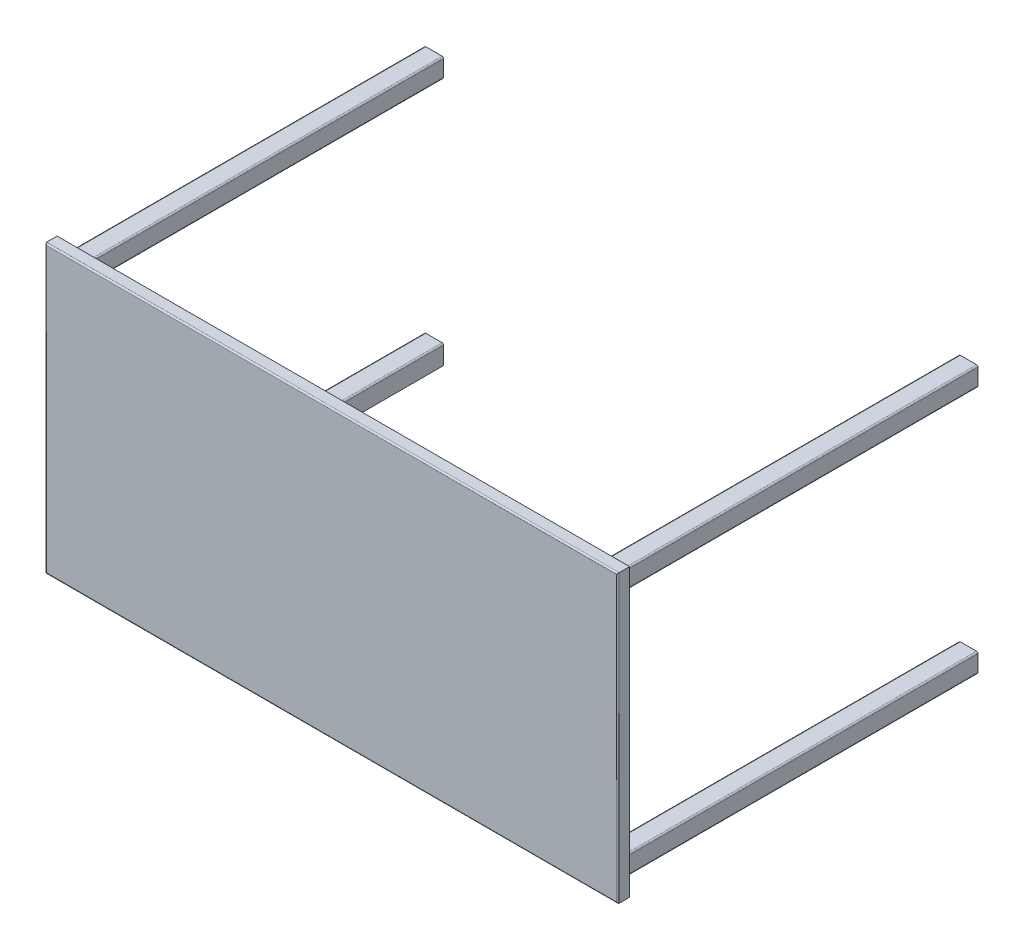
SolidWorks part; units mm, degrees
ref_plane "前视基准面" through (0, 0, 0) normal (0, 0, 1) x (1, 0, 0)
ref_plane "上视基准面" through (0, 0, 0) normal (0, 1, 0) x (1, 0, 0)
ref_plane "右视基准面" through (0, 0, 0) normal (1, 0, 0) x (0, 0, -1)
other "Configuration Table"
sketch "Sketch1" plane through (0, 0, 0) normal (0, 0, 1) x (1, 0, 0)
  line L1 (-600, -300) -> (600, -300)
  line L2 (-600, -300) -> (-600, 300)
  line L3 (-600, 300) -> (600, 300)
  line L4 (600, -300) -> (600, 300)
  line L5 (-600, -300) -> (600, 300) construction
  line L6 (-600, 300) -> (600, -300) construction
  point P0 (0, 0)
extrude "Boss-Extrude1" add sketch "Sketch1" along normal blind 25
sketch "Sketch2" plane through (0, 0, 0) normal (0, 0, 1) x (1, 0, 0)
  line L1 (-580, 240) -> (-540, 240)
  line L2 (-580, 240) -> (-580, 280)
  line L3 (-580, 280) -> (-540, 280)
  line L4 (-540, 240) -> (-540, 280)
  line L5 (-580, 240) -> (-540, 280) construction
  line L6 (-580, 280) -> (-540, 240) construction
  line L7 (540, 240) -> (580, 240)
  line L8 (540, 240) -> (540, 280)
  line L9 (540, 280) -> (580, 280)
  line L10 (580, 240) -> (580, 280)
  line L11 (540, 240) -> (580, 280) construction
  line L12 (540, 280) -> (580, 240) construction
  line L13 (-580, -280) -> (-540, -280)
  line L14 (-580, -280) -> (-580, -240)
  line L15 (-580, -240) -> (-540, -240)
  line L16 (-540, -280) -> (-540, -240)
  line L17 (-580, -280) -> (-540, -240) construction
  line L18 (-580, -240) -> (-540, -280) construction
  line L19 (540, -280) -> (580, -280)
  line L20 (540, -280) -> (540, -240)
  line L21 (540, -240) -> (580, -240)
  line L22 (580, -280) -> (580, -240)
  line L23 (540, -280) -> (580, -240) construction
  line L24 (540, -240) -> (580, -280) construction
  point P0 (-560, 260)
  point P5 (560, 260)
  point P10 (-560, -260)
  point P15 (560, -260)
extrude "Boss-Extrude2" add sketch "Sketch2" against normal blind 750
fillet "Fillet1" radius 3 16 edges at (540, -240, -375) (580, -240, -375) (580, -280, -375) (-580, -240, -375) (-540, -240, -375) (-580, -280, -375) (540, 280, -375) (580, 280, -375) (580, 240, -375) (-580, 280, -375) (-540, 280, -375) (-540, 240, -375) (-600, 0, 25) (600, 0, 25) (0, -300, 25) (0, 300, 25)
